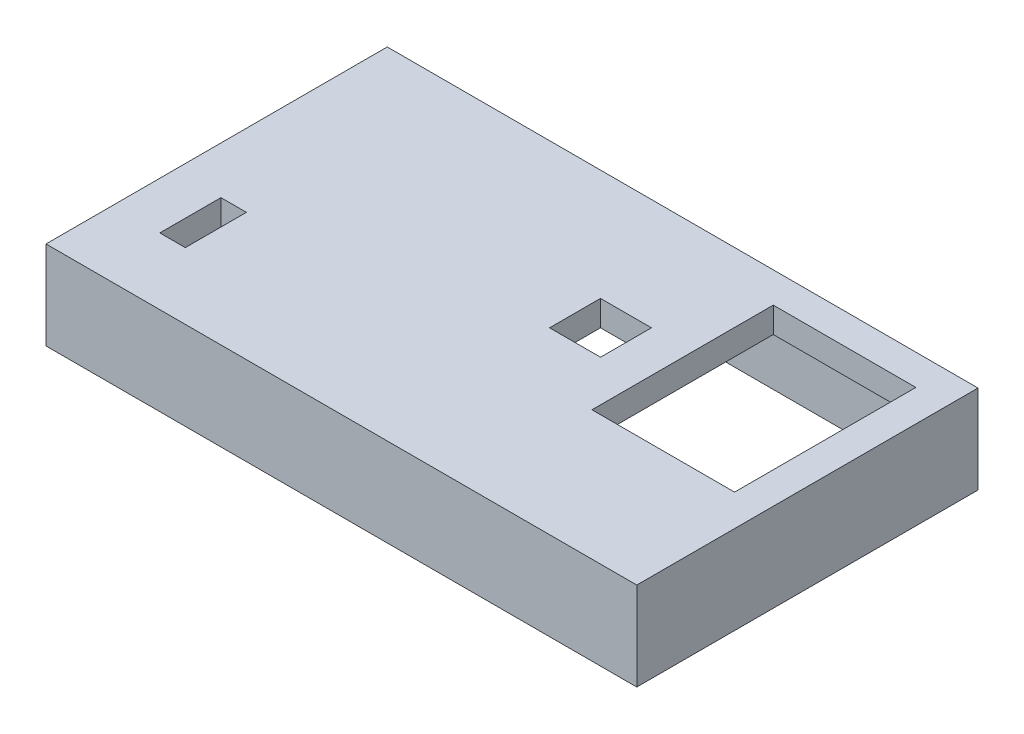
SolidWorks part; units mm, degrees
ref_plane "Front Plane" through (0, 0, 0) normal (0, 0, 1) x (1, 0, 0)
ref_plane "Top Plane" through (0, 0, 0) normal (0, 1, 0) x (1, 0, 0)
ref_plane "Right Plane" through (0, 0, 0) normal (1, 0, 0) x (0, 0, -1)
sketch "Sketch1" plane through (0, 0, 0) normal (0, 1, 0) x (1, 0, 0)
  line L1 (0, 0) -> (116, 0)
  line L2 (0, 0) -> (0, 67)
  line L3 (0, 67) -> (116, 67)
  line L4 (116, 0) -> (116, 67)
  dimension "D1" = 116
  dimension "D2" = 67
extrude "Boss-Extrude1" add sketch "Sketch1" along normal blind 5
sketch "Sketch2" plane through (0, 0, 0) normal (0, -1, 0) x (1, 0, 0)
  line L0 (0, -67) -> (0, 0) construction
  line L1 (3, -3) -> (113, -3)
  line L2 (3, -3) -> (3, -64)
  line L3 (3, -64) -> (113, -64)
  line L4 (113, -3) -> (113, -64)
  line L5 (0, 0) -> (116, 0) construction
  line L6 (116, 0) -> (116, -67) construction
  line L7 (116, -67) -> (0, -67) construction
  line L8 (0, 0) -> (0, -67)
  line L9 (0, -67) -> (116, -67)
  line L10 (116, 0) -> (116, -67)
  line L11 (0, 0) -> (116, 0)
  dimension "D1" = 3
  dimension "D2" = 3
  dimension "D3" = 3
  dimension "D4" = 3
  dimension "D5" = 3
extrude "Boss-Extrude2" add sketch "Sketch2" along normal blind 12.35
sketch "Sketch3" plane through (0, 0, 0) normal (0, -1, 0) x (1, 0, 0)
  line L5 (3, -64) -> (113, -64) construction
  line L6 (81.8, -25.4) -> (109.8, -25.4)
  line L7 (81.8, -25.4) -> (81.8, -61)
  line L8 (81.8, -61) -> (109.8, -61)
  line L9 (109.8, -25.4) -> (109.8, -61)
  line L10 (113, -64) -> (113, -3) construction
  dimension "D1" = 35.6
  dimension "D2" = 28
  dimension "D3" = 3
  dimension "D4" = 3.2
extrude "Cut-Extrude1" cut sketch "Sketch3" against normal through all
sketch "Sketch4" plane through (0, 0, 0) normal (0, -1, 0) x (1, 0, 0)
  line L0 (81.8, -25.4) -> (81.8, -61) construction
  line L1 (63.7, -35.18) -> (73.7, -35.18)
  line L2 (63.7, -35.18) -> (63.7, -45.18)
  line L3 (63.7, -45.18) -> (73.7, -45.18)
  line L4 (73.7, -35.18) -> (73.7, -45.18)
  line L5 (3, -64) -> (113, -64) construction
  dimension "D1" = 10
  dimension "D2" = 10
  dimension "D3" = 8.1
  dimension "D4" = 18.82
extrude "Cut-Extrude2" cut sketch "Sketch4" against normal through all
sketch "Sketch5" plane through (0, 0, 0) normal (0, -1, 0) x (1, 0, 0)
  line L0 (113, -3) -> (3, -3) construction
  line L1 (9.3, -13.05) -> (14.3, -13.05)
  line L2 (9.3, -13.05) -> (9.3, -25.05)
  line L3 (9.3, -25.05) -> (14.3, -25.05)
  line L4 (14.3, -13.05) -> (14.3, -25.05)
  line L5 (3, -3) -> (3, -64) construction
  dimension "D1" = 5
  dimension "D2" = 12
  dimension "D3" = 10.05
  dimension "D4" = 6.3
extrude "Cut-Extrude3" cut sketch "Sketch5" against normal through all
